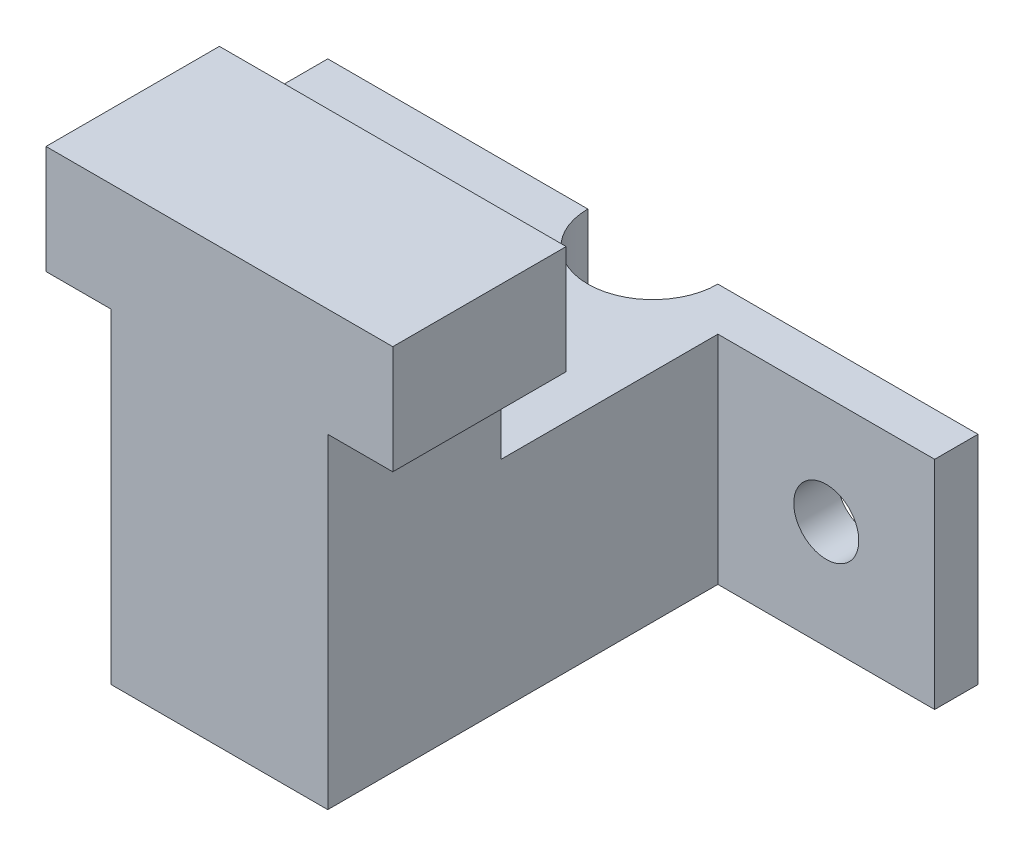
SolidWorks part; units mm, degrees
ref_plane "Front Plane" through (0, 0, 0) normal (0, 0, 1) x (1, 0, 0)
ref_plane "Top Plane" through (0, 0, 0) normal (0, 1, 0) x (1, 0, 0)
ref_plane "Right Plane" through (0, 0, 0) normal (1, 0, 0) x (0, 0, -1)
sketch "Sketch3" plane through (0, 0, 0) normal (0, 0, 1) x (1, 0, 0)
  line L1 (-8, -10) -> (8, -10)
  line L2 (-8, -10) -> (-8, 10)
  line L3 (-8, 10) -> (8, 10)
  line L4 (8, -10) -> (8, 10)
  line L5 (-8, -10) -> (8, 10) construction
  line L6 (-8, 10) -> (8, -10) construction
  point P0 (0, 0)
  dimension "D1" = 20
  dimension "D2" = 16
extrude "Boss-Extrude1" add sketch "Sketch3" along normal blind 8
sketch "Sketch4" plane through (0, 0, 8) normal (0, 0, 1) x (1, 0, 0)
  line L1 (-8, -10) -> (-5, -10)
  line L2 (-8, -10) -> (-8, 5)
  line L3 (-8, 5) -> (-5, 5)
  line L4 (-5, -10) -> (-5, 5)
  line L5 (8, -10) -> (5, -10)
  line L6 (8, -10) -> (8, 5)
  line L7 (8, 5) -> (5, 5)
  line L8 (5, -10) -> (5, 5)
  dimension "D1" = 3
  dimension "D2" = 3
  dimension "D3" = 15
  dimension "D4" = 15
extrude "Cut-Extrude1" cut sketch "Sketch4" against normal blind 8
sketch "Sketch5" plane through (0, 0, 0) normal (0, 0, -1) x (-1, 0, 0)
  line L0 (-5, 5) -> (-5, -10) construction
  line L1 (5, -10) -> (-5, -10)
  line L2 (5, -10) -> (5, 0)
  line L3 (5, 0) -> (-5, 0)
  line L4 (-5, -10) -> (-5, 0)
  dimension "D1" = 10
extrude "Boss-Extrude2" add sketch "Sketch5" along normal blind 12
sketch "Sketch6" plane through (0, -10, 0) normal (0, -1, 0) x (1, 0, 0)
  line L0 (5, -12) -> (-5, -12) construction
  circle A0 centre (0, -12) radius 3
  dimension "D1" = 6
extrude "Cut-Extrude2" cut sketch "Sketch6" against normal blind 14
sketch "Sketch8" plane through (5, 0, 0) normal (1, 0, 0) x (0, 0, -1)
  line L0 (12, 0) -> (0, 0) construction
  line L1 (12, -10) -> (10, -10)
  line L2 (12, -10) -> (12, 0)
  line L3 (12, 0) -> (10, 0)
  line L4 (10, -10) -> (10, 0)
  dimension "D1" = 2
extrude "Boss-Extrude3" add sketch "Sketch8" along normal blind 10
sketch "Sketch9" plane through (-5, 0, 0) normal (-1, 0, 0) x (0, 0, 1)
  line L0 (-12, 0) -> (0, 0) construction
  line L1 (-12, -10) -> (-10, -10)
  line L2 (-12, -10) -> (-12, 0)
  line L3 (-12, 0) -> (-10, 0)
  line L4 (-10, -10) -> (-10, 0)
  dimension "D1" = 2
extrude "Boss-Extrude4" add sketch "Sketch9" along normal blind 10
sketch "Sketch10" plane through (0, 0, -12) normal (0, 0, -1) x (-1, 0, 0)
  line L0 (3, -10) -> (15, -10) construction
  line L1 (15, 0) -> (15, -10) construction
  line L2 (-15, -10) -> (-15, 0) construction
  line L3 (-15, -10) -> (-3, -10) construction
  circle A0 centre (-10, -5) radius 1.5
  circle A1 centre (10, -5) radius 1.5
  dimension "D1" = 3
  dimension "D2" = 3
  dimension "D3" = 5
  dimension "D4" = 5
  dimension "D5" = 5
  dimension "D6" = 5
extrude "Cut-Extrude3" cut sketch "Sketch10" against normal blind 10
